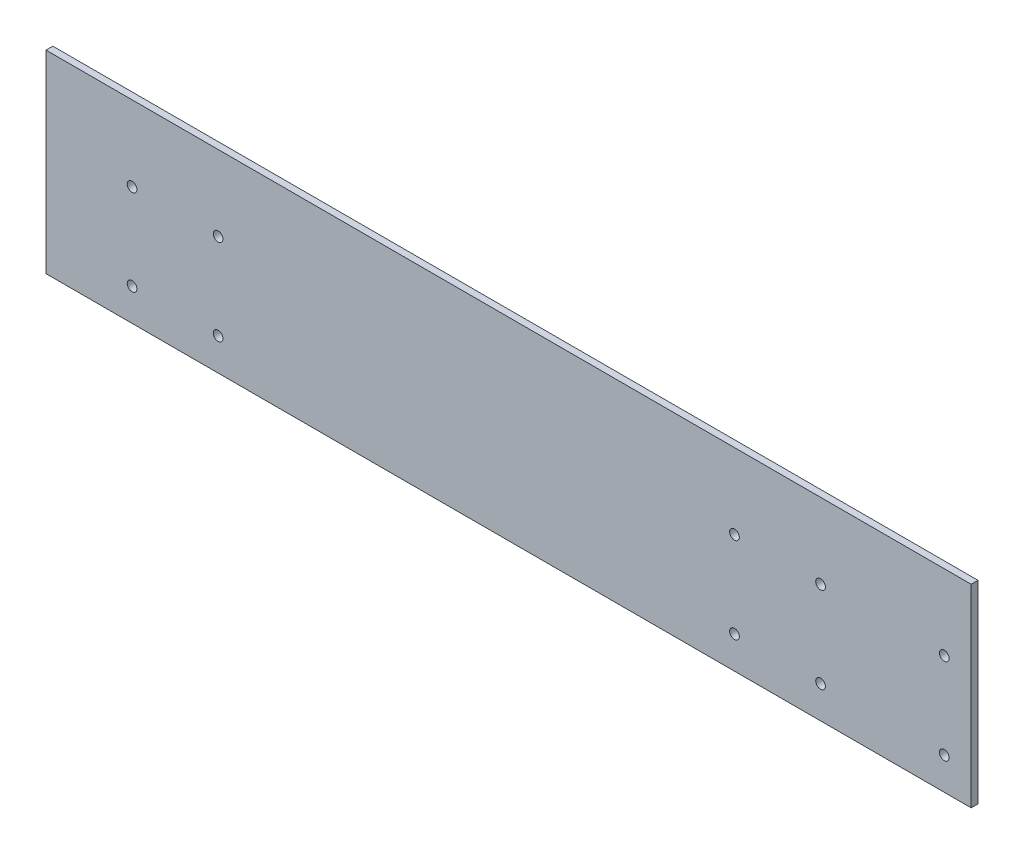
SolidWorks part; units mm, degrees
ref_plane "Front Plane" through (0, 0, 0) normal (0, 0, 1) x (1, 0, 0)
ref_plane "Top Plane" through (0, 0, 0) normal (0, 1, 0) x (1, 0, 0)
ref_plane "Right Plane" through (0, 0, 0) normal (1, 0, 0) x (0, 0, -1)
sketch "Sketch3" plane through (0, 0, 0) normal (0, 0, 1) x (1, 0, 0)
  line L1 (-215, -45) -> (215, -45)
  line L2 (-215, -45) -> (-215, 45)
  line L3 (-215, 45) -> (215, 45)
  line L4 (215, -45) -> (215, 45)
  line L5 (-215, -45) -> (215, 45) construction
  line L6 (-215, 45) -> (215, -45) construction
  point P0 (0, 0)
  dimension "D1" = 430
  dimension "D2" = 90
extrude "Boss-Extrude1" add sketch "Sketch3" along normal blind 3.175
hole_wizard "M4 Clearance Hole1" positions "Sketch4" profile "Sketch5" hole size "M4" standard "ANSI Metric" end condition through all
sketch "Sketch4" plane through (0, 0, 3.175) normal (0, 0, 1) x (1, 0, 0)
  line L1 (-175, -30) -> (-135, -30)
  line L2 (-175, -30) -> (-175, 10)
  line L3 (-175, 10) -> (-135, 10)
  line L4 (-135, -30) -> (-135, 10)
  line L5 (-175, -30) -> (-135, 10) construction
  line L6 (-175, 10) -> (-135, -30) construction
  line L7 (-215, -45) -> (215, -45) construction
  line L8 (105, -30) -> (145, -30)
  line L9 (105, -30) -> (105, 10)
  line L10 (105, 10) -> (145, 10)
  line L11 (145, -30) -> (145, 10)
  line L12 (105, -30) -> (145, 10) construction
  line L13 (105, 10) -> (145, -30) construction
  line L14 (202.5, 10) -> (202.5, -30)
  line L16 (215, -45) -> (215, 45) construction
  point P2 (-135, 10)
  point P37 (-175, -30)
  point P38 (-175, 10)
  point P39 (-135, -30)
  point P41 (-155, -10)
  point P48 (145, 10)
  point P49 (105, -30)
  point P50 (105, 10)
  point P51 (145, -30)
  point P52 (202.5, 10)
  point P53 (202.5, -30)
  point P71 (125, -10)
  dimension "D1" = 40
  dimension "D2" = 40
  dimension "D3" = 35
  dimension "D4" = 60
  dimension "D6" = 40
  dimension "D7" = 12.5
  dimension "D8" = 90
  dimension "D5" = 2
sketch "Sketch5" plane through (-135, 10, 3.175) normal (1, 0, 0) x (0, -1, 0)
  line L0 (0, 0) -> (0, 3.175)
  line L1 (0, 3.175) -> (2.25, 3.175)
  line L2 (2.25, 3.175) -> (2.25, 0)
  line L5 (2.25, 0) -> (0, 0)
  line L11 (0, -6.35) -> (0, 107.95) construction
  dimension "Thru Hole Dia." = 4.5
  dimension "Thru Hole Depth" = 3.175
